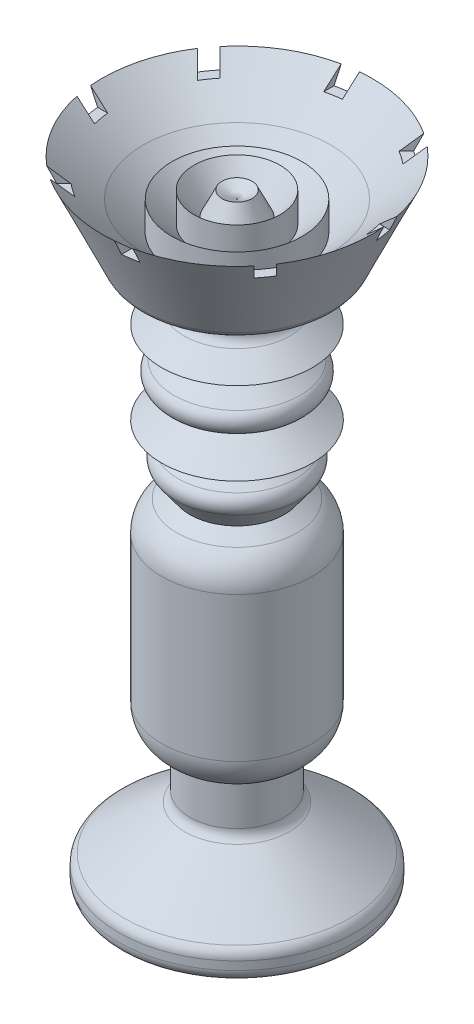
SolidWorks part; units mm, degrees
ref_plane "Front Plane" through (0, 0, 0) normal (0, 0, 1) x (1, 0, 0)
ref_plane "Top Plane" through (0, 0, 0) normal (0, 1, 0) x (1, 0, 0)
ref_plane "Right Plane" through (0, 0, 0) normal (1, 0, 0) x (0, 0, -1)
sketch "Sketch1" plane through (0, 0, 0) normal (0, 0, 1) x (1, 0, 0)
  line L0 (0, 32.9485) -> (0, -89.2439)
  line L1 (0, -89.2439) -> (24.1614, -89.2439)
  line L2 (24.1614, -89.2439) -> (24.1614, -83.7107)
  line L3 (24.1614, -83.7107) -> (9.6366, -73.1053)
  line L4 (9.6366, -73.1053) -> (9.6366, -63.4221)
  line L5 (9.6366, -63.4221) -> (15.4004, -60.6555)
  line L6 (15.4004, -60.6555) -> (15.4004, -46.1307)
  line L7 (15.4004, -46.1307) -> (15.4004, -35.2948)
  line L8 (15.4004, -35.2948) -> (15.4004, -22.3839)
  line L9 (15.4004, -22.3839) -> (9.6366, -18.1754)
  line L10 (9.6366, -18.1754) -> (14.0373, -12.1483)
  line L11 (14.0373, -12.1483) -> (9.6366, -8.9351)
  line L12 (9.6366, -8.9351) -> (15.4004, -6.1684)
  line L13 (15.4004, -6.1684) -> (5.3478, 0)
  line L14 (5.3478, 0) -> (19.1854, 0)
  line L15 (19.1854, 0) -> (8.7995, 7.5834)
  line L16 (8.7995, 7.5834) -> (15.4004, 10.7518)
  line L17 (15.4004, 10.7518) -> (7.4023, 16.5917)
  line L18 (7.4023, 16.5917) -> (19.1854, 22.2476)
  line L19 (19.1854, 22.2476) -> (27.6318, 40.5313)
  line L20 (19.1854, 32.9485) -> (13.2939, 27.0569)
  line L21 (13.2939, 27.0569) -> (13.2939, 32.9485)
  line L22 (13.2939, 32.9485) -> (8.7995, 28.4542)
  line L23 (8.7995, 28.4542) -> (8.7995, 34.5624)
  line L24 (8.7995, 34.5624) -> (5.3478, 29.835)
  line L25 (5.3478, 29.835) -> (3.0786, 34.5624)
  line L26 (3.0786, 34.5624) -> (0, 32.9485)
  line L27 (27.6318, 40.5313) -> (19.1854, 32.9485)
revolve "Revolve2" add sketch "Sketch1" angle 360 about L0
fillet "Fillet1" radius 7.62 1 edges at (0, -22.3839, 15.4004)
fillet "Fillet2" radius 7.62 1 edges at (0, -60.6555, 15.4004)
fillet "Fillet3" radius 2.54 1 edges at (0, -73.1053, 9.6366)
fillet "Fillet4" radius 2.54 2 edges at (0, -89.2439, 24.1614) (0, -83.7107, 24.1614)
fillet "Fillet7" radius 2.54 1 edges at (0, 0, 19.1854)
fillet "Fillet8" radius 2.54 1 edges at (0, -12.1483, 14.0373)
fillet "Fillet9" radius 2.54 2 edges at (0, 16.5917, 7.4023) (0, 22.2476, 19.1854)
sketch "Sketch2" plane through (0, 0, 0) normal (0, 0, 1) x (1, 0, 0)
  line L1 (-5.7109, 43.7667) -> (-2.4466, 43.7667)
  line L2 (-5.7109, 43.7667) -> (-5.7109, 37.3913)
  line L3 (-5.7109, 37.3913) -> (-2.4466, 37.3913)
  line L4 (-2.4466, 43.7667) -> (-2.4466, 37.3913)
extrude "Cut-Extrude3" cut sketch "Sketch2" against normal blind 41.402
pattern_circular "CirPattern3" count 8 over 360 about axis through (0, 0, 0) along (0, 1, 0) of "Cut-Extrude3"
